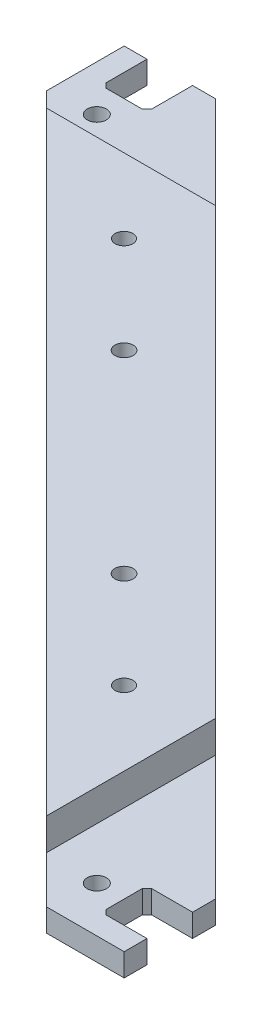
SolidWorks part; units mm, degrees
ref_plane "Front Plane" through (0, 0, 0) normal (0, 0, 1) x (1, 0, 0)
ref_plane "Top Plane" through (0, 0, 0) normal (0, 1, 0) x (1, 0, 0)
ref_plane "Right Plane" through (0, 0, 0) normal (1, 0, 0) x (0, 0, -1)
sketch "Sketch1" plane through (0, 0, 0) normal (0, 1, 0) x (1, 0, 0)
  line L0 (0, 0) -> (20, 0)
  line L1 (0, 0) -> (0, -17)
  line L2 (0, -17) -> (155, -172)
  line L3 (155, -172) -> (172, -172)
  line L4 (172, -172) -> (172, -152)
  line L5 (172, -152) -> (20, 0)
  point P7 (0, 0)
  dimension "D1" = 135
  dimension "D2" = 20
  dimension "D3" = 17
  dimension "D5" = 155
extrude "Main Base Extrude" add sketch "Sketch1" along normal blind 12
sketch "Sketch3" plane through (0, 12, 0) normal (0, 1, 0) x (1, 0, 0)
  line L0 (172, -152) -> (20, 0) construction
  line L1 (0, 0) -> (47.3, 0)
  line L2 (0, 0) -> (0, -27.3)
  line L3 (0, -27.3) -> (47.3, -27.3)
  line L4 (47.3, 0) -> (47.3, -27.3)
  line L6 (172, -172) -> (144.7, -172)
  line L7 (172, -172) -> (172, -124.7)
  line L8 (172, -124.7) -> (144.7, -124.7)
  line L9 (144.7, -172) -> (144.7, -124.7)
  dimension "D1" = 27.3
extrude "Track Seat Cut" cut sketch "Sketch3" against normal blind 7
sketch "Sketch2" plane through (0, 12, 0) normal (0, 1, 0) x (1, 0, 0)
  line L4 (10, -16) -> (0, -16) construction
  line L5 (0, 0) -> (0, -17) construction
  line L6 (156, -162) -> (156, -172) construction
  line L7 (155, -172) -> (172, -172) construction
  line L8 (10, -16) -> (10, 0) construction
  line L9 (20, 0) -> (0, 0) construction
  line L10 (156, -162) -> (172, -162) construction
  line L11 (172, -172) -> (172, -152) construction
  circle A0 centre (10, -16) radius 2.1
  circle A1 centre (156, -162) radius 2.1
  dimension "D3" = 4.2
  dimension "D1" = 146
  dimension "D2" = 146
  dimension "D4" = 10
extrude "Track Connect Holes" cut sketch "Sketch2" against normal through all
sketch "Sketch5" plane through (0, 0, 0) normal (0, 1, 0) x (1, 0, 0)
  line L0 (13.2353, -13.2647) -> (159.2353, -159.2647) construction
  line L1 (10.3, -27.3) -> (144.7, -161.7) construction
  line L2 (83.0319, -88.9681) -> (58.0319, -113.9681) construction
  line L3 (144.7, -124.7) -> (47.3, -27.3) construction
  circle A0 centre (128.4117, -128.4411) radius 1.95
  circle A1 centre (107.1985, -107.2279) radius 2
  circle A2 centre (43.5589, -43.5883) radius 1.95
  circle A3 centre (64.7721, -64.8015) radius 2
  point P19 (96, -76)
  dimension "D3" = 3.9
  dimension "D4" = 4
  dimension "D1" = 30
  dimension "D2" = 60
  dimension "D5" = 12
extrude "Wall Spaced Holes" cut sketch "Sketch5" along normal through all both and the other way through all
sketch "Sketch9" plane through (0, 5, 0) normal (0, 1, 0) x (1, 0, 0)
  line L0 (172, -172) -> (172, -152) construction
  line L1 (5, 0) -> (15, 0)
  line L2 (5, 0) -> (5, -10)
  line L3 (5, -10) -> (15, -10)
  line L4 (15, 0) -> (15, -10)
  line L5 (20, 0) -> (0, 0) construction
  line L6 (172, -167) -> (162, -167)
  line L7 (172, -167) -> (172, -157)
  line L8 (172, -157) -> (162, -157)
  line L9 (162, -167) -> (162, -157)
  line L15 (155, -172) -> (172, -172) construction
  line L16 (0, 0) -> (0, -17) construction
  point P4 (0, 0)
  point P5 (0, 0)
  dimension "D1" = 5
  dimension "D2" = 10
  dimension "D3" = 10
  dimension "D4" = 5
extrude "Wire Passthrough Cut" cut sketch "Sketch9" against normal through all
chamfer "Wire Passthrough Chamfer" distance 1 angle 45 4 edges at (162, 2.5, 167) (162, 2.5, 157) (15, 2.5, 10) (5, 2.5, 10)
